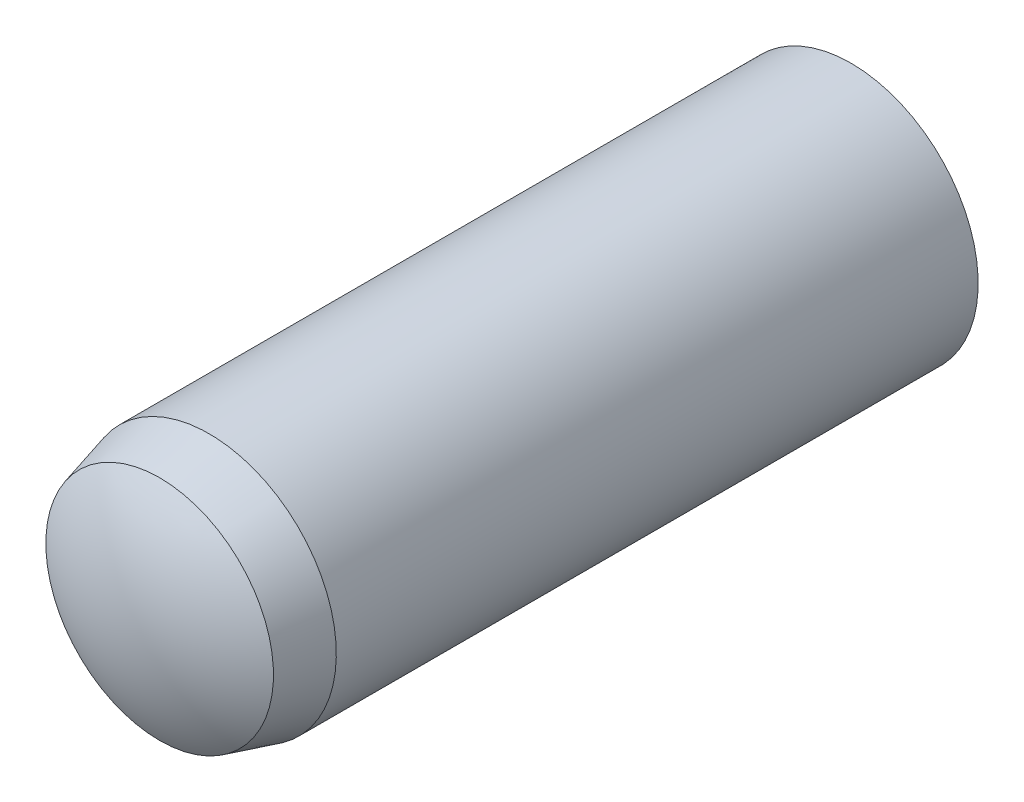
SolidWorks part; units mm, degrees
ref_plane "Front Plane" through (0, 0, 0) normal (0, 0, 1) x (1, 0, 0)
ref_plane "Top Plane" through (0, 0, 0) normal (0, 1, 0) x (1, 0, 0)
ref_plane "Right Plane" through (0, 0, 0) normal (1, 0, 0) x (0, 0, -1)
sketch "Sketch1" plane through (0, 0, 0) normal (0, 0, 1) x (1, 0, 0)
  circle A0 centre (0, 0) radius 1
  point P3 (0, 1)
  dimension "Diameter" = 2
sketch "Sketch2" plane through (0, 0, 0) normal (1, 0, 0) x (0, 0, -1)
  line L0 (-3, 0) -> (3, 0) construction
  line L1 (-3, 0) -> (-3, 1) construction
  line L2 (-3, 1) -> (3, 1)
  line L3 (3, 1) -> (3, 0) construction
  line L4 (-2.74, 0.8955) -> (-2.35, 1)
  arc A0 (-3, 0) -> (-2.74, 0.8955) centre (-1.3278, 0) cw
  arc A1 (3, 0) -> (2.7, 1) centre (1.1833, 0) ccw
  point P2 (0, 0)
  point P11 (-1, 0)
  point P13 (1, 0)
  dimension "Length" = 6
  dimension "D1" = 15
  dimension "D2" = 0.3
  dimension "D3" = 0.65
  dimension "D4" = 0.39
  dimension "D5" = 2
  dimension "D6" = 2
sketch "Sketch3" plane through (0, 0, 0) normal (1, 0, 0) x (0, 0, -1)
  line L0 (-3, 0) -> (3, 0) construction
  line L1 (-2.74, 0.8955) -> (-2.35, 1) construction
  line L2 (-3, 0) -> (3, 0)
  line L3 (-2.74, 0.8955) -> (-2.35, 1)
  line L4 (-2.35, 1) -> (2.7, 1)
  arc A0 (3, 0) -> (2.7, 1) centre (1.1833, 0) ccw construction
  arc A1 (-2.74, 0.8955) -> (-3, 0) centre (-1.3278, 0) ccw construction
  arc A2 (3, 0) -> (2.7, 1) centre (1.1833, 0) ccw
  arc A3 (-2.74, 0.8955) -> (-3, 0) centre (-1.3278, 0) ccw
revolve "Revolve1" add sketch "Sketch3" angle 360 about L2
ref_plane "Plan1" through (0, 0, -3) normal (0, 0, 1) x (1, 0, 0)
equation "\"D2@Sketch2\" = \"Diameter@Sketch1\" * .15"
equation "\"D3@Sketch2\" = \"Diameter@Sketch1\" * .325"
equation "\"D4@Sketch2\" = \"D3@Sketch2\" * .6"
equation "\"D5@Sketch2\"=\"Diameter@Sketch1\""
equation "\"D6@Sketch2\"=\"D5@sketch2\""
